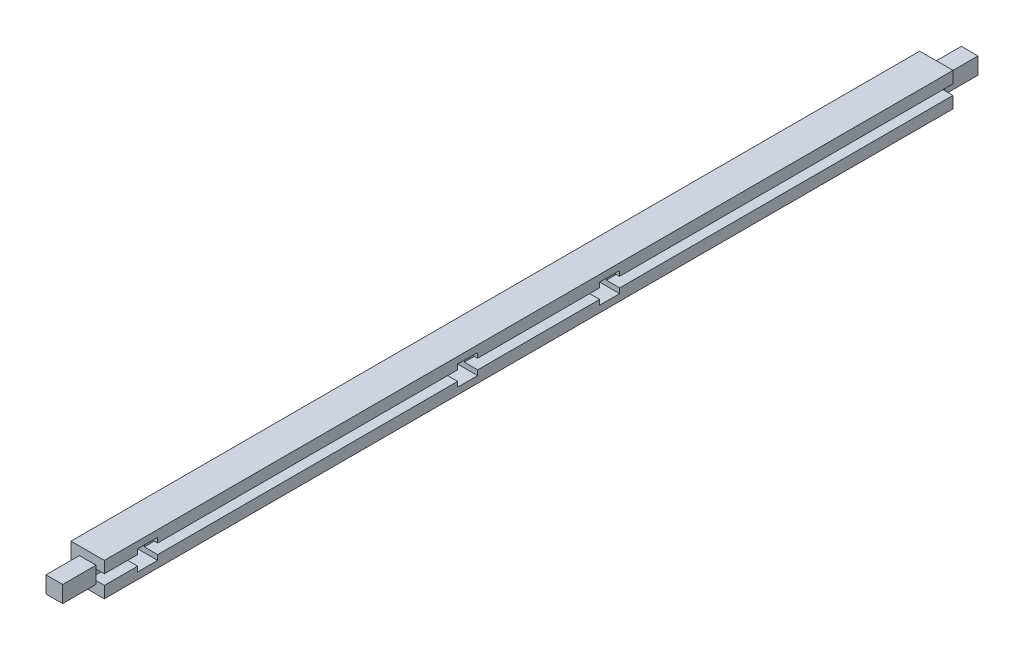
SolidWorks part; units mm, degrees
ref_plane "Front Plane" through (0, 0, 0) normal (0, 0, 1) x (1, 0, 0)
ref_plane "Top Plane" through (0, 0, 0) normal (0, 1, 0) x (1, 0, 0)
ref_plane "Right Plane" through (0, 0, 0) normal (1, 0, 0) x (0, 0, -1)
sketch "Sketch1" plane through (0, 0, 0) normal (0, 0, 1) x (1, 0, 0)
  line L1 (0, 0) -> (5, 0)
  line L2 (0, 0) -> (0, 5)
  line L3 (0, 5) -> (5, 5)
  line L4 (5, 0) -> (5, 5)
  dimension "D1" = 5
  dimension "D2" = 5
extrude "Boss-Extrude1" add sketch "Sketch1" along normal blind 127.3
sketch "Sketch2" plane through (0, 0, 0) normal (0, 0, -1) x (-1, 0, 0)
  line L0 (-5, 0) -> (-5, 5) construction
  line L1 (-3.75, 1.25) -> (-1.25, 1.25)
  line L2 (-3.75, 1.25) -> (-3.75, 3.75)
  line L3 (-3.75, 3.75) -> (-1.25, 3.75)
  line L4 (-1.25, 1.25) -> (-1.25, 3.75)
  line L5 (-5, 5) -> (0, 5) construction
  dimension "D1" = 2.5
  dimension "D2" = 2.5
  dimension "D3" = 1.25
  dimension "D4" = 1.25
extrude "Boss-Extrude2" add sketch "Sketch2" along normal blind 5
sketch "Sketch3" plane through (0, 0, 127.3) normal (0, 0, 1) x (1, 0, 0)
  line L0 (0, 5) -> (0, 0) construction
  line L1 (1.25, 1.25) -> (3.75, 1.25)
  line L2 (1.25, 1.25) -> (1.25, 3.75)
  line L3 (1.25, 3.75) -> (3.75, 3.75)
  line L4 (3.75, 1.25) -> (3.75, 3.75)
  line L5 (5, 5) -> (0, 5) construction
  dimension "D1" = 2.5
  dimension "D2" = 2.5
  dimension "D3" = 1.25
  dimension "D4" = 1.25
extrude "Boss-Extrude3" add sketch "Sketch3" along normal blind 5
sketch "Sketch4" plane through (0, 0, 0) normal (-1, 0, 0) x (0, 0, 1)
  line L0 (127.3, 5) -> (0, 5) construction
  line L1 (119.3, 1) -> (122.3, 1)
  line L2 (119.3, 1) -> (119.3, 4)
  line L3 (119.3, 4) -> (122.3, 4)
  line L4 (122.3, 1) -> (122.3, 4)
  line L5 (127.3, 5) -> (127.3, 0) construction
  line L6 (0, 5) -> (0, 0) construction
  line L7 (50, 4) -> (53, 4)
  line L8 (50, 4) -> (50, 1)
  line L9 (50, 1) -> (53, 1)
  line L10 (53, 4) -> (53, 1)
  line L12 (71.3, 4) -> (74.3, 4)
  line L13 (71.3, 4) -> (71.3, 1)
  line L14 (71.3, 1) -> (74.3, 1)
  line L15 (74.3, 4) -> (74.3, 1)
  point P18 (74.3, 2.5)
  dimension "D1" = 3
  dimension "D2" = 3
  dimension "D3" = 1
  dimension "D4" = 5
  dimension "D5" = 3
  dimension "D6" = 3
  dimension "D7" = 1
  dimension "D8" = 50
  dimension "D9" = 3
  dimension "D10" = 3
  dimension "D11" = 1
  dimension "D12" = 45
extrude "Cut-Extrude1" cut sketch "Sketch4" against normal blind 30
sketch "Sketch7" plane through (5, 0, 0) normal (1, 0, 0) x (0, 0, -1)
  line L0 (-127.3, 1.25) -> (-127.3, 3.75) construction
  line L1 (-127.3, 1.75) -> (0, 1.75)
  line L2 (-127.3, 1.75) -> (-127.3, 3.25)
  line L3 (-127.3, 3.25) -> (0, 3.25)
  line L4 (0, 1.75) -> (0, 3.25)
  line L5 (-127.3, 0) -> (-127.3, 5) construction
  line L6 (0, 0) -> (0, 5) construction
  line L7 (-127.3, 5) -> (0, 5) construction
  dimension "D1" = 1.5
  dimension "D2" = 1.75
extrude "Cut-Extrude5" cut sketch "Sketch7" against normal blind 2
